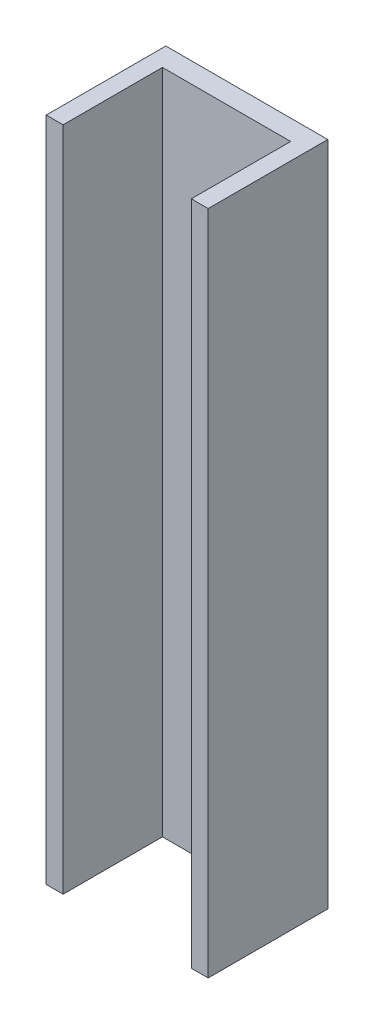
SolidWorks part; units mm, degrees
ref_plane "Front Plane" through (0, 0, 0) normal (0, 0, 1) x (1, 0, 0)
ref_plane "Top Plane" through (0, 0, 0) normal (0, 1, 0) x (1, 0, 0)
ref_plane "Right Plane" through (0, 0, 0) normal (1, 0, 0) x (0, 0, -1)
sketch "Sketch2" plane through (0, 0, 0) normal (0, 1, 0) x (1, 0, 0)
  line L0 (-3.8, 0) -> (3.8, 0)
  line L1 (-3.8, 0) -> (-3.8, -5.89)
  line L2 (3.8, 0) -> (3.8, -5.89)
  line L3 (3.8, -5.89) -> (4.8, -5.89)
  line L4 (4.8, -5.89) -> (4.8, 1.2)
  line L5 (4.8, 1.2) -> (-4.8, 1.2)
  line L6 (-4.8, 1.2) -> (-4.8, -5.89)
  line L7 (-4.8, -5.89) -> (-3.8, -5.89)
  point P3 (0, 0)
  dimension "D1" = 7.6
  dimension "D2" = 5.89
  dimension "D3" = 1
  dimension "D4" = 1
  dimension "D5" = 1.2
extrude "Boss-Extrude1" add sketch "Sketch2" along normal blind 39.5
sketch "Sketch3" plane through (0, 0, -1.2) normal (0, 0, -1) x (-1, 0, 0)
  line L0 (-4.8, 39.5) -> (-4.8, 0) construction
  circle A0 centre (0, 19.75) radius 1.3375
  point P5 (-4.8, 19.75)
  dimension "D1" = 2.675
extrude "Cut-Extrude1" cut sketch "Sketch3" against normal blind 40.1
